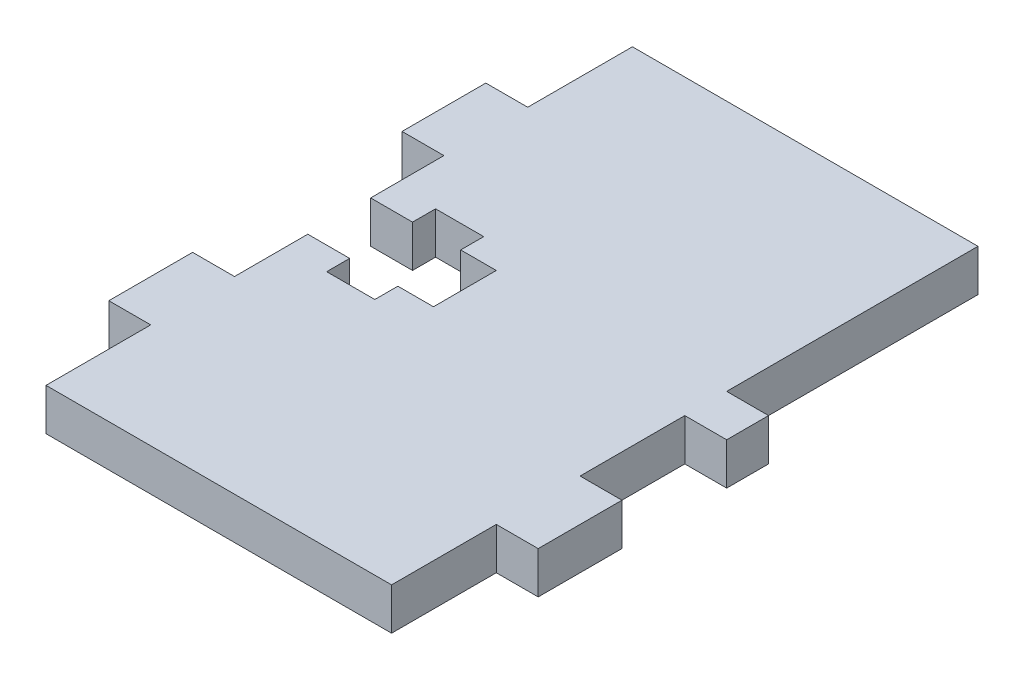
SolidWorks part; units mm, degrees
ref_plane "Front Plane" through (0, 0, 0) normal (0, 0, 1) x (1, 0, 0)
ref_plane "Top Plane" through (0, 0, 0) normal (0, 1, 0) x (1, 0, 0)
ref_plane "Right Plane" through (0, 0, 0) normal (1, 0, 0) x (0, 0, -1)
sketch "Sketch1" plane through (0, 0, 0) normal (0, 1, 0) x (1, 0, 0)
  line L0 (0, 14) -> (16.5, 14) construction
  line L1 (0, 0) -> (16.5, 0)
  line L2 (0, 0) -> (0, 5)
  line L3 (0, 28) -> (16.5, 28)
  line L4 (16.5, 0) -> (16.5, 5)
  line L5 (8.25, 28) -> (8.25, 0) construction
  line L6 (4.3, 12.5) -> (4.3, 11.4)
  line L7 (0, 23) -> (-2, 23)
  line L9 (0, 19) -> (-2, 19)
  line L10 (-2, 23) -> (-2, 19)
  line L11 (6, 12.5) -> (4.3, 12.5)
  line L12 (6, 12.5) -> (6, 15.5)
  line L13 (6, 15.5) -> (4.3, 15.5)
  line L15 (6, 12.5) -> (0, 15.5) construction
  line L16 (6, 15.5) -> (0, 12.5) construction
  line L18 (2, 15.5) -> (2, 16.6)
  line L19 (2, 16.6) -> (4.3, 16.6)
  line L20 (4.3, 15.5) -> (4.3, 16.6)
  line L21 (2, 11.4) -> (4.3, 11.4)
  line L22 (2, 12.5) -> (2, 11.4)
  line L23 (0, 9) -> (-2, 9)
  line L24 (-2, 5) -> (-2, 9)
  line L25 (0, 5) -> (-2, 5)
  line L26 (0, 23) -> (0, 28)
  line L27 (2, 15.5) -> (0, 15.5)
  line L28 (0, 15.5) -> (0, 19)
  line L29 (2, 12.5) -> (0, 12.5)
  line L30 (0, 9) -> (0, 12.5)
  line L31 (16.5, 5) -> (18.5, 5)
  line L32 (18.5, 5) -> (18.5, 9)
  line L33 (16.5, 9) -> (18.5, 9)
  line L34 (16.5, 9) -> (16.5, 14)
  line L35 (16.5, 14) -> (18.5, 14)
  line L37 (16.5, 16) -> (18.5, 16)
  line L38 (18.5, 14) -> (18.5, 16)
  line L39 (16.5, 16) -> (16.5, 28)
  point P13 (3, 14)
  dimension "D1" = 2
  dimension "D2" = 4
  dimension "D3" = 5
  dimension "D4" = 3
  dimension "D5" = 1.1
  dimension "D6" = 2
  dimension "D7" = 2.3
  dimension "D8" = 6
  dimension "D9" = 28
  dimension "D10" = 16.5
  dimension "D11" = 2
extrude "Boss-Extrude1" add sketch "Sketch1" along normal blind 2
